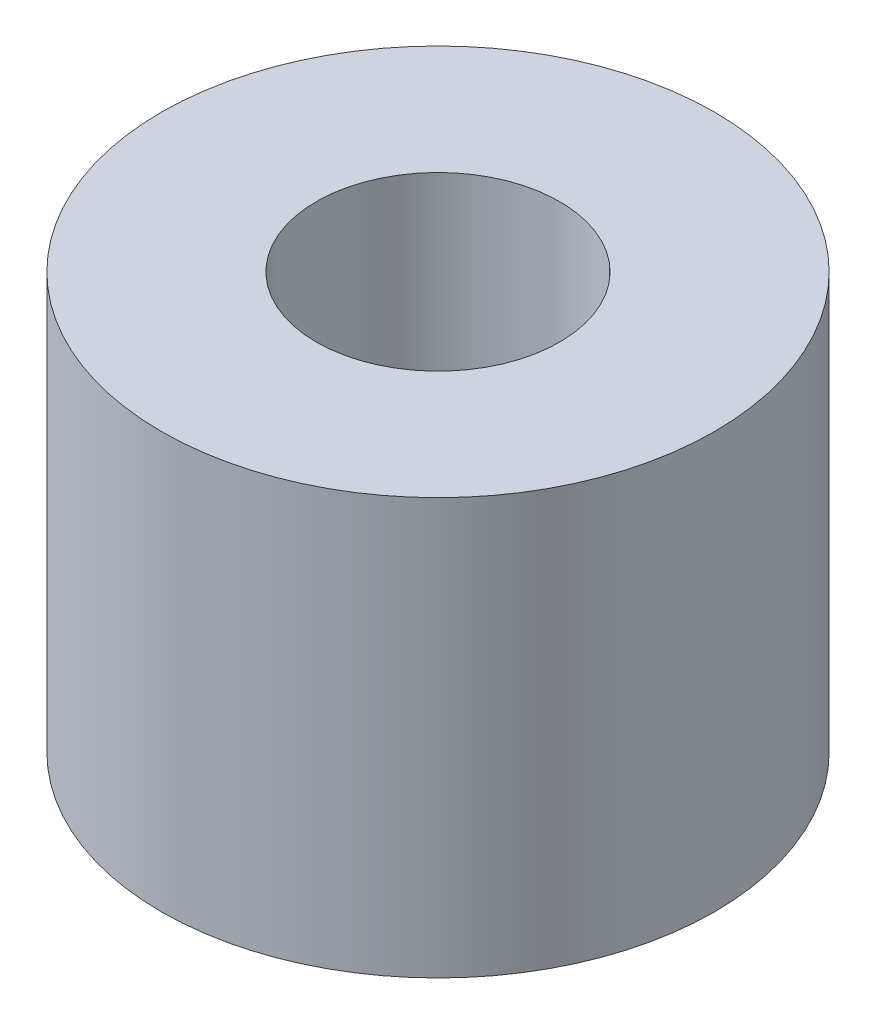
SolidWorks part; units mm, degrees
material "Stainless Steel (ferritic)"
ref_plane "Ön Düzlem" through (0, 0, 0) normal (0, 0, 1) x (1, 0, 0)
ref_plane "Üst Düzlem" through (0, 0, 0) normal (0, 1, 0) x (1, 0, 0)
ref_plane "Sağ Düzlem" through (0, 0, 0) normal (1, 0, 0) x (0, 0, -1)
sketch "Sketch1" plane through (0, 0, 0) normal (0, 1, 0) x (1, 0, 0)
  circle A0 centre (0, 0) radius 11
  circle A1 centre (0, 0) radius 25
  dimension "D1" = 22
  dimension "D2" = 50
extrude "Boss-Extrude1" add sketch "Sketch1" along normal blind 37.6
